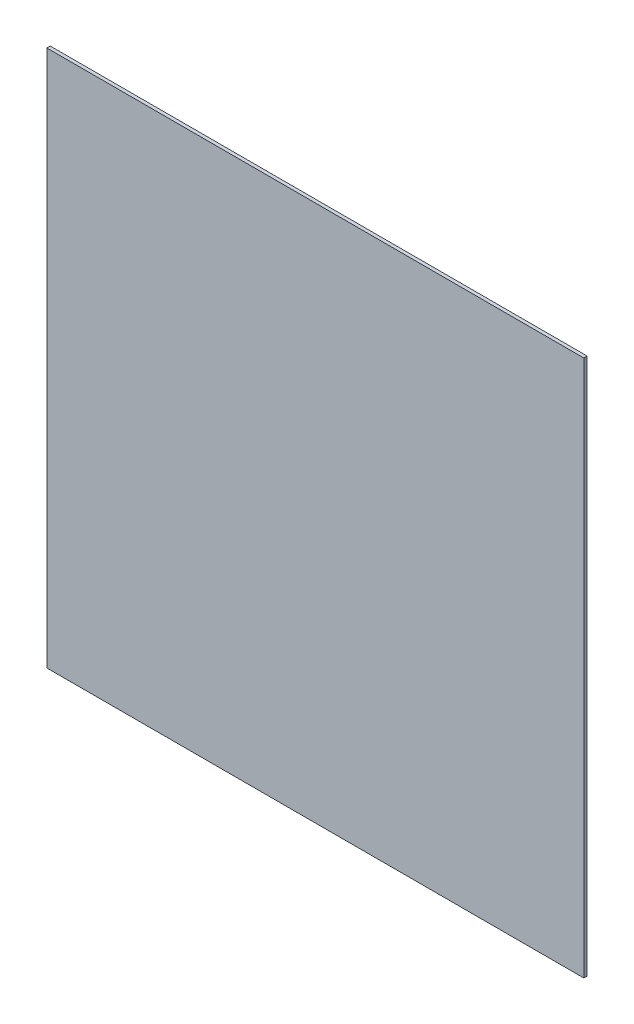
SolidWorks part; units mm, degrees
material "Zoltek Panex 33"
ref_plane "Front Plane" through (0, 0, 0) normal (0, 0, 1) x (1, 0, 0)
ref_plane "Top Plane" through (0, 0, 0) normal (0, 1, 0) x (1, 0, 0)
ref_plane "Right Plane" through (0, 0, 0) normal (1, 0, 0) x (0, 0, -1)
sketch "Sketch1" plane through (0, 0, 0) normal (0, 0, 1) x (1, 0, 0)
  line L0 (-15.875, 15.875) -> (15.875, -15.875) construction
  line L1 (-15.875, 15.875) -> (15.875, 15.875)
  line L2 (-15.875, 15.875) -> (-15.875, -15.875)
  line L3 (-15.875, -15.875) -> (15.875, -15.875)
  line L4 (15.875, 15.875) -> (15.875, -15.875)
  dimension "D1" = 31.75
  dimension "D2" = 31.75
extrude "Extrude1" add sketch "Sketch1" along normal blind 0.2
